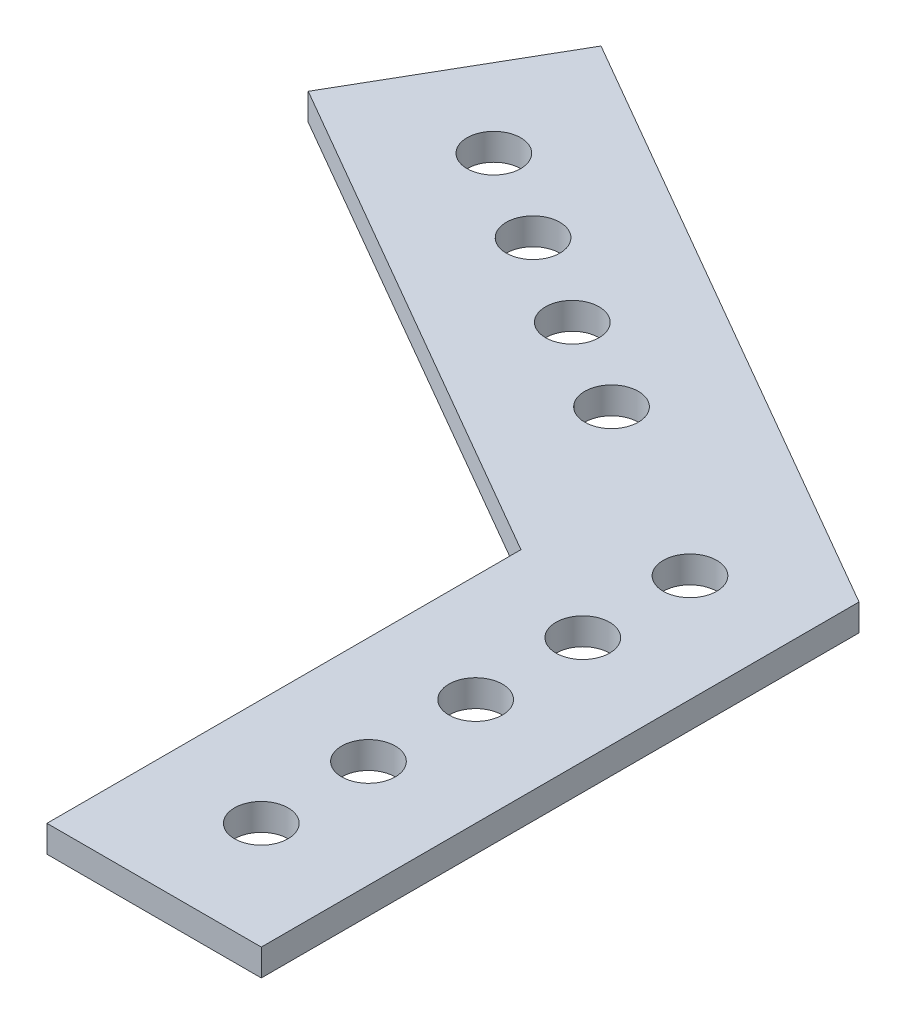
SolidWorks part; units mm, degrees
ref_plane "Front Plane" through (0, 0, 0) normal (0, 0, 1) x (1, 0, 0)
ref_plane "Top Plane" through (0, 0, 0) normal (0, 1, 0) x (1, 0, 0)
ref_plane "Right Plane" through (0, 0, 0) normal (1, 0, 0) x (0, 0, -1)
sketch "Sketch1" plane through (0, 0, 0) normal (0, 1, 0) x (1, 0, 0)
  line L0 (0, 0) -> (0, -63.5) construction
  line L1 (0, 0) -> (-65.9911, 38.1) construction
  line L2 (12.7, 7.3323) -> (12.7, -63.5)
  line L3 (12.7, 7.3323) -> (-59.6411, 49.0985)
  line L4 (-12.7, -7.3323) -> (-72.3411, 27.1015)
  line L5 (-12.7, -7.3323) -> (-12.7, -63.5)
  line L6 (-72.3411, 27.1015) -> (-59.6411, 49.0985)
  line L7 (-12.7, -63.5) -> (12.7, -63.5)
  dimension "D1" = 76.2
  dimension "D2" = 63.5
  dimension "D5" = 120
  dimension "D3" = 12.7
  dimension "D4" = 12.7
extrude "Boss-Extrude1" add sketch "Sketch1" along normal blind 3.175
sketch "Sketch2" plane through (0, 3.175, 0) normal (0, 1, 0) x (1, 0, 0)
  line L0 (-65.9911, 38.1) -> (0, 0) construction
  line L1 (-59.6411, 49.0985) -> (-72.3411, 27.1015) construction
  line L2 (0, 0) -> (0, -63.5) construction
  line L3 (-12.7, -63.5) -> (12.7, -63.5) construction
  circle A0 centre (-54.9926, 31.75) radius 3.175
  circle A1 centre (-43.9941, 25.4) radius 3.175
  circle A2 centre (-32.9956, 19.05) radius 3.175
  circle A3 centre (-21.997, 12.7) radius 3.175
  circle A4 centre (0, 0) radius 3.175
  circle A6 centre (0, -50.8) radius 3.175
  circle A7 centre (0, -38.1) radius 3.175
  circle A8 centre (0, -25.4) radius 3.175
  circle A9 centre (0, -12.7) radius 3.175
  arc A10 (-13.7482, 7.9375) -> (-8.2489, 4.7625) centre (-10.9985, 6.35) ccw [skipped]
  dimension "D1" = 6.35
  dimension "D2" = 12.7
  dimension "D3" = 5
extrude "Cut-Extrude1" cut sketch "Sketch2" against normal through all
